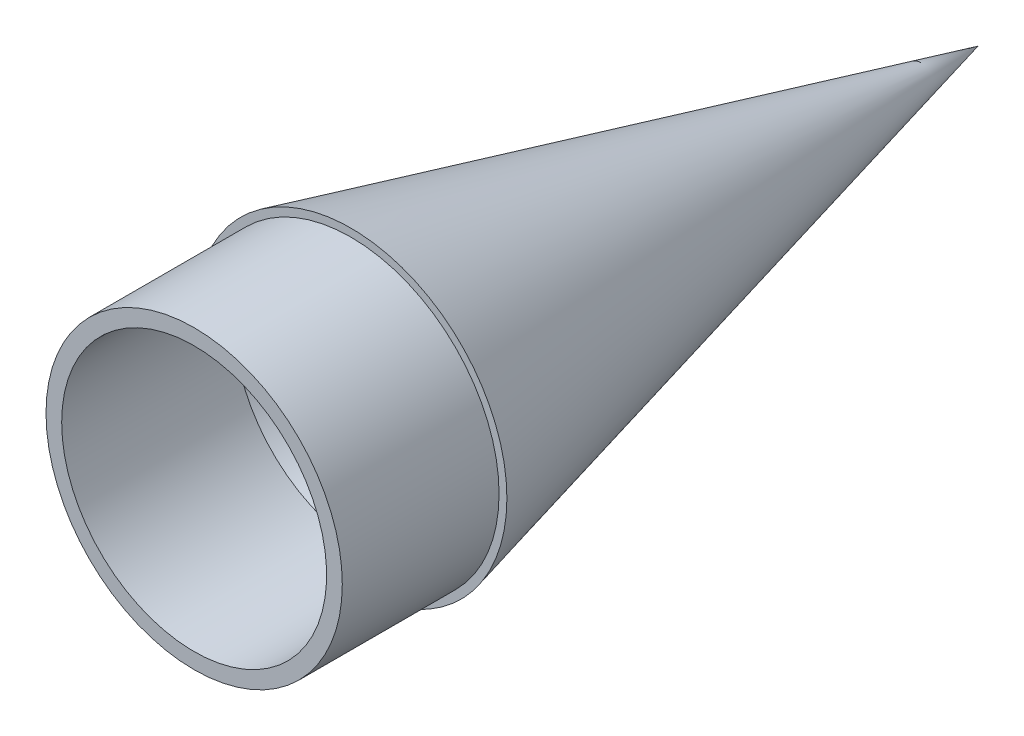
SolidWorks part; units mm, degrees
material "ABS"
ref_plane "Спереди" through (0, 0, 0) normal (0, 0, 1) x (1, 0, 0)
ref_plane "Сверху" through (0, 0, 0) normal (0, 1, 0) x (1, 0, 0)
ref_plane "Справа" through (0, 0, 0) normal (1, 0, 0) x (0, 0, -1)
sketch "Эскиз1" plane through (0, 0, 0) normal (0, 1, 0) x (1, 0, 0)
  line L0 (0, 0) -> (0, 80) construction
  line L1 (0, 0) -> (-19.9, 0) construction
  line L2 (0, 80) -> (-19.9, 0)
  line L3 (-19.9, 0) -> (-18.9, 0)
  line L4 (-18.9, 0) -> (-18.9, -20)
  line L5 (-17.6437, -20) -> (0, -20)
  line L6 (0, -20) -> (0, 80)
  line L7 (-17.6437, -20) -> (-18.9, -20)
  dimension "D1" = 19.9
  dimension "D2" = 1
  dimension "D3" = 20
  dimension "D4" = 18.9
  dimension "D5" = 100
revolve "Повернуть1" add sketch "Эскиз1" angle 360 about L6
shell "Оболочка1" thickness 2
